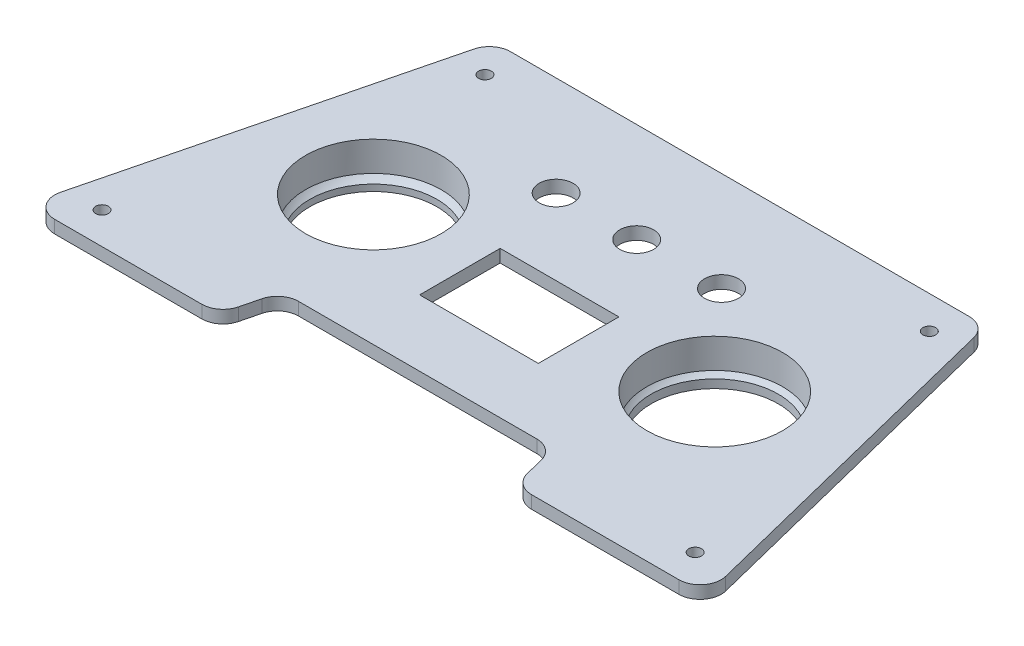
SolidWorks part; units mm, degrees
ref_plane "Ön Düzlem" through (0, 0, 0) normal (0, 0, 1) x (1, 0, 0)
ref_plane "Üst Düzlem" through (0, 0, 0) normal (0, 1, 0) x (1, 0, 0)
ref_plane "Sağ Düzlem" through (0, 0, 0) normal (1, 0, 0) x (0, 0, -1)
sketch "Çizim1" plane through (0, 0, 0) normal (0, 1, 0) x (1, 0, 0)
  line L0 (3.9039, 0) -> (112.0961, 0)
  line L1 (116.9468, -3.7873) -> (136.4468, -81.7873)
  line L2 (131.5961, -88) -> (96.9039, -88)
  line L3 (92.0532, -84.2127) -> (90.9468, -79.7873)
  line L4 (86.0961, -76) -> (29.9039, -76)
  line L5 (25.0532, -79.7873) -> (23.9468, -84.2127)
  line L6 (19.0961, -88) -> (-15.5961, -88)
  line L7 (-20.4468, -81.7873) -> (-0.9468, -3.7873)
  line L8 (58, 0) -> (58, -76) construction
  arc A0 (23.9468, -84.2127) -> (19.0961, -88) centre (19.0961, -83) cw
  arc A1 (96.9039, -88) -> (92.0532, -84.2127) centre (96.9039, -83) cw
  arc A2 (29.9039, -76) -> (25.0532, -79.7873) centre (29.9039, -81) ccw
  arc A3 (90.9468, -79.7873) -> (86.0961, -76) centre (86.0961, -81) ccw
  arc A4 (131.5961, -88) -> (136.4468, -81.7873) centre (131.5961, -83) ccw
  arc A5 (-15.5961, -88) -> (-20.4468, -81.7873) centre (-15.5961, -83) cw
  arc A6 (116.9468, -3.7873) -> (112.0961, 0) centre (112.0961, -5) ccw
  arc A7 (3.9039, 0) -> (-0.9468, -3.7873) centre (3.9039, -5) ccw
  point P18 (23, -88)
  point P21 (93, -88)
  point P28 (138, -88)
  point P31 (-22, -88)
  point P34 (116, 0)
  point P37 (0, 0)
  dimension "D6" = 5
  dimension "D7" = 5
  dimension "D1" = 116
  dimension "D2" = 160
  dimension "D3" = 76
  dimension "D4" = 12
  dimension "D5" = 45
extrude "Yükseklik-Ekstrüzyon1" add sketch "Çizim1" along normal blind 3
sketch "Çizim2" plane through (0, 3, 0) normal (0, 1, 0) x (1, 0, 0)
  line L0 (54.41, 0) -> (54.41, -76) construction
  line L1 (112.0961, 0) -> (3.9039, 0) construction
  line L3 (16.91, -45.35) -> (97.41, -45.35) construction
  circle A0 centre (16.91, -45.35) radius 16
  circle A1 centre (97.41, -45.35) radius 16
  point P4 (0, 0)
  point P5 (0, 0)
  point P10 (0, 0)
  dimension "D2" = 32
  dimension "D1" = 80.5
  dimension "D3" = 45.35
  dimension "D4" = 43
  dimension "D5" = 54.41
extrude "Kes-Ekstrüzyon1" cut sketch "Çizim2" against normal blind 10
sketch "Çizim3" plane through (0, 3, 0) normal (0, 1, 0) x (1, 0, 0)
  line L0 (112.0961, 0) -> (3.9039, 0) construction
  line L1 (58, -76) -> (58, 0) construction
  line L2 (29.9039, -76) -> (86.0961, -76) construction
  line L3 (-15.5961, -88) -> (19.0961, -88) construction
  circle A0 centre (5.6, -7.73) radius 1.5
  circle A1 centre (-11.94, -80.5) radius 1.5
  circle A2 centre (127.94, -80.5) radius 1.5
  circle A3 centre (110.4, -7.73) radius 1.5
  point P4 (58, 0)
  point P13 (1.75, -88)
  dimension "D1" = 3
  dimension "D4" = 3
  dimension "D5" = 7.5
  dimension "D2" = 7.73
  dimension "D3" = 52.4
  dimension "D6" = 13.69
extrude "Kes-Ekstrüzyon2" cut sketch "Çizim3" against normal blind 10
sketch "Çizim4" plane through (0, 3, 0) normal (0, 1, 0) x (1, 0, 0)
  line L0 (38.16, -23.5) -> (77.16, -23.5) construction
  line L2 (112.0961, 0) -> (3.9039, 0) construction
  line L3 (16.91, -45.35) -> (97.41, -45.35) construction
  line L4 (57.16, -23.5) -> (57.16, -45.35) construction
  circle A0 centre (38.16, -23.5) radius 4
  circle A1 centre (57.16, -23.5) radius 4
  circle A2 centre (77.16, -23.5) radius 4
  dimension "D2" = 8
  dimension "D1" = 23.5
  dimension "D3" = 19
  dimension "D4" = 20
extrude "Kes-Ekstrüzyon3" cut sketch "Çizim4" against normal blind 10
sketch "Çizim5" plane through (0, 3, 0) normal (0, 1, 0) x (1, 0, 0)
  line L0 (57.16, -23.5) -> (57.16, -76) construction
  line L1 (43.16, -40.8) -> (71.16, -40.8)
  line L2 (43.16, -40.8) -> (43.16, -63.8)
  line L3 (43.16, -63.8) -> (71.16, -63.8)
  line L4 (71.16, -40.8) -> (71.16, -63.8)
  line L6 (29.9039, -76) -> (86.0961, -76) construction
  circle A0 centre (38.16, -23.5) radius 4 construction
  dimension "D1" = 23
  dimension "D2" = 28
  dimension "D3" = 17.3
extrude "Kes-Ekstrüzyon4" cut sketch "Çizim5" against normal blind 10
sketch "Çizim6" plane through (0, 3, 0) normal (0, 1, 0) x (1, 0, 0)
  line L0 (71.16, -40.8) -> (43.16, -40.8) construction
  line L1 (40.66, -36.8) -> (73.66, -36.8)
  line L2 (40.66, -36.8) -> (40.66, -67.8)
  line L3 (40.66, -67.8) -> (73.66, -67.8)
  line L4 (73.66, -36.8) -> (73.66, -67.8)
  line L5 (43.16, -40.8) -> (43.16, -63.8) construction
  line L6 (71.16, -63.8) -> (71.16, -40.8) construction
  line L7 (43.16, -63.8) -> (71.16, -63.8) construction
  dimension "D1" = 4
  dimension "D2" = 2.5
  dimension "D3" = 2.5
  dimension "D4" = 4
extrude "Kes-Ekstrüzyon5" cut sketch "Çizim6" against normal blind 1.5
sketch "Çizim7" plane through (0, 0, 0) normal (0, -1, 0) x (1, 0, 0)
  circle A0 centre (97.41, 45.35) radius 16
  circle A1 centre (97.41, 45.35) radius 18
  circle A2 centre (16.91, 45.35) radius 16
  circle A3 centre (16.91, 45.35) radius 18
  circle A5 centre (97.41, 45.35) radius 16 construction
  circle A6 centre (16.91, 45.35) radius 16 construction
  dimension "D1" = 2
  dimension "D2" = 2
extrude "Yükseklik-Ekstrüzyon2" add sketch "Çizim7" along normal blind 4
ref_plane "Düzlem1" through (0, 0, 45.35) normal (0, 0, 1) x (1, 0, 0)
sketch "Çizim8" plane through (0, 0, 45.35) normal (0, 0, 1) x (1, 0, 0)
  line L0 (97.41, -4) -> (97.41, -32.97) construction
  line L1 (79.41, -4) -> (115.41, -4) construction
  line L2 (115.41, -4) -> (113.4256, -4) construction
  line L3 (112.41, -5.0156) -> (112.41, -7)
  line L4 (81.41, -4) -> (113.41, -4) construction
  line L5 (115.41, -4) -> (113.4256, -4)
  arc A0 (112.41, -7) -> (115.41, -4) centre (106.9999, 1.4101) ccw
  arc A1 (112.41, -5.0156) -> (113.4256, -4) centre (106.9999, 1.4101) ccw
  arc A2 (113.4405, -6.2396) -> (115.41, -4) centre (106.9999, 1.4101) ccw construction
  arc A4 (112.41, -5.0156) -> (114.0644, -3.1344) centre (106.9999, 1.4101) ccw construction
  point P15 (0, 0)
  point P16 (0, 0)
  dimension "D2" = 10
  dimension "D4" = 3
  dimension "D1" = 8.4
  dimension "D3" = 15
revolve "Döndür1" add sketch "Çizim8" angle 360 about L0
sketch "Çizim9" plane through (0, 0, 45.35) normal (0, 0, 1) x (1, 0, 0)
  line L0 (16.91, -4) -> (16.91, -29.7004) construction
  line L1 (0.91, -4) -> (32.91, -4) construction
  line L2 (31.91, -5.4733) -> (31.91, -7)
  line L3 (34.91, -4) -> (33.3833, -4)
  line L4 (34.91, -4) -> (35.6229, -4) construction
  line L5 (34.2007, -2.7551) -> (35.6229, -2.7551) construction
  line L6 (-1.09, -4) -> (34.91, -4) construction
  arc A0 (34.91, -4) -> (31.91, -7) centre (26.4999, 1.4101) cw
  arc A1 (33.3833, -4) -> (31.91, -5.4733) centre (26.4999, 1.4101) cw
  arc A2 (34.2007, -2.7551) -> (31.91, -5.4733) centre (26.4999, 1.4101) cw construction
  arc A3 (34.91, -4) -> (32.6793, -6.4521) centre (26.4999, 1.4101) cw construction
  point P7 (28.5, -4)
  point P10 (33.4189, -9.0183)
  dimension "D2" = 10
  dimension "D3" = 3
  dimension "D4" = 8.7551
  dimension "D1" = 15
revolve "Döndür2" add sketch "Çizim9" angle 360 about L0
fillet "Radyus1" radius 1 2 edges at (16.91, 0, 27.35) (97.41, 0, 27.35)
sketch "Çizim10" plane through (0, 0, 0) normal (0, -1, 0) x (-1, 0, 0)
  line L0 (-70.36, -40.8) -> (-70.36, -56.3)
  line L1 (-71.16, -40.8) -> (-70.36, -40.8)
  line L2 (-71.16, -40.8) -> (-71.16, -63.8)
  line L3 (-71.16, -63.8) -> (-43.16, -63.8)
  line L4 (-43.16, -56.3) -> (-43.16, -63.8)
  line L5 (-70.36, -56.3) -> (-43.16, -56.3)
  dimension "D1" = 0.8
  dimension "D2" = 7.5
extrude "Yükseklik-Ekstrüzyon3" add sketch "Çizim10" against normal up to vertex
sketch "Çizim11" plane through (0, 0, 0) normal (0, -1, 0) x (1, 0, 0)
  line L0 (42.86, 40.5) -> (42.86, 56.3)
  line L1 (70.36, 40.8) -> (43.16, 40.8)
  line L2 (70.36, 40.8) -> (70.36, 40.5)
  line L3 (70.36, 40.5) -> (42.86, 40.5)
  line L5 (42.86, 56.3) -> (43.16, 56.3)
  line L6 (43.16, 56.3) -> (43.16, 40.8)
  line L7 (43.16, 56.3) -> (43.16, 40.8) construction
  dimension "D1" = 0.3
  dimension "D2" = 0.3
extrude "Kes-Ekstrüzyon6" cut sketch "Çizim11" against normal blind 4
sketch "Çizim12" plane through (0, 1.5, 0) normal (0, 1, 0) x (1, 0, 0)
  line L0 (42.86, -40.5) -> (42.86, -56.3) construction
  line L1 (42.86, -38.9) -> (70.86, -38.9)
  line L2 (42.86, -38.9) -> (42.86, -57.9)
  line L3 (42.86, -57.9) -> (70.86, -57.9)
  line L4 (70.86, -38.9) -> (70.86, -57.9)
  line L5 (42.86, -48.4) -> (70.36, -48.4) construction
  line L6 (70.36, -56.3) -> (70.36, -40.5) construction
  dimension "D1" = 19
  dimension "D2" = 28
extrude "Kes-Ekstrüzyon7" cut sketch "Çizim12" against normal blind 10
sketch "Çizim13" plane through (0, 1.5, 0) normal (0, 1, 0) x (1, 0, 0)
  line L0 (42.86, -57.9) -> (70.86, -57.9) construction
  line L1 (70.86, -57.9) -> (70.86, -38.9) construction
  line L2 (42.86, -38.9) -> (42.86, -57.9) construction
  line L3 (70.86, -38.9) -> (42.86, -38.9) construction
  line L4 (40.66, -36.8) -> (40.66, -67.8)
  line L5 (40.66, -67.8) -> (73.66, -67.8)
  line L6 (73.66, -67.8) -> (73.66, -36.8)
  line L7 (73.66, -36.8) -> (40.66, -36.8)
  line L8 (40.66, -36.8) -> (40.66, -67.8)
  line L9 (40.66, -67.8) -> (73.66, -67.8)
  line L10 (73.66, -67.8) -> (73.66, -36.8)
  line L11 (73.66, -36.8) -> (40.66, -36.8)
  line L12 (42.86, -57.9) -> (70.86, -57.9)
  line L13 (70.86, -57.9) -> (70.86, -38.9)
  line L14 (42.86, -38.9) -> (42.86, -57.9)
  line L15 (70.86, -38.9) -> (42.86, -38.9)
  dimension "D1" = 0
extrude "Yükseklik-Ekstrüzyon4" add sketch "Çizim13" along normal up to vertex (1.5 mm away)
sketch "Çizim14" plane through (0, 3, 0) normal (0, 1, 0) x (1, 0, 0)
  line L0 (70.86, -57.9) -> (70.86, -38.9) construction
  line L1 (42.86, -57.9) -> (70.86, -57.9)
  line L2 (42.86, -57.9) -> (42.86, -60.4)
  line L3 (42.86, -60.4) -> (70.86, -60.4)
  line L4 (70.86, -57.9) -> (70.86, -60.4)
  dimension "D1" = 2.5
extrude "Kes-Ekstrüzyon8" cut sketch "Çizim14" against normal blind 10
sketch "Çizim15" plane through (0, 3, 0) normal (0, 1, 0) x (1, 0, 0)
  line L0 (70.86, -60.4) -> (70.86, -38.9) construction
  line L1 (42.86, -38.9) -> (70.86, -38.9)
  line L2 (42.86, -38.9) -> (42.86, -41.4)
  line L3 (42.86, -41.4) -> (70.86, -41.4)
  line L4 (70.86, -38.9) -> (70.86, -41.4)
  dimension "D1" = 2.5
extrude "Yükseklik-Ekstrüzyon5" add sketch "Çizim15" against normal up to vertex (3 mm away) up to point (42.86, 0, 60.4)
